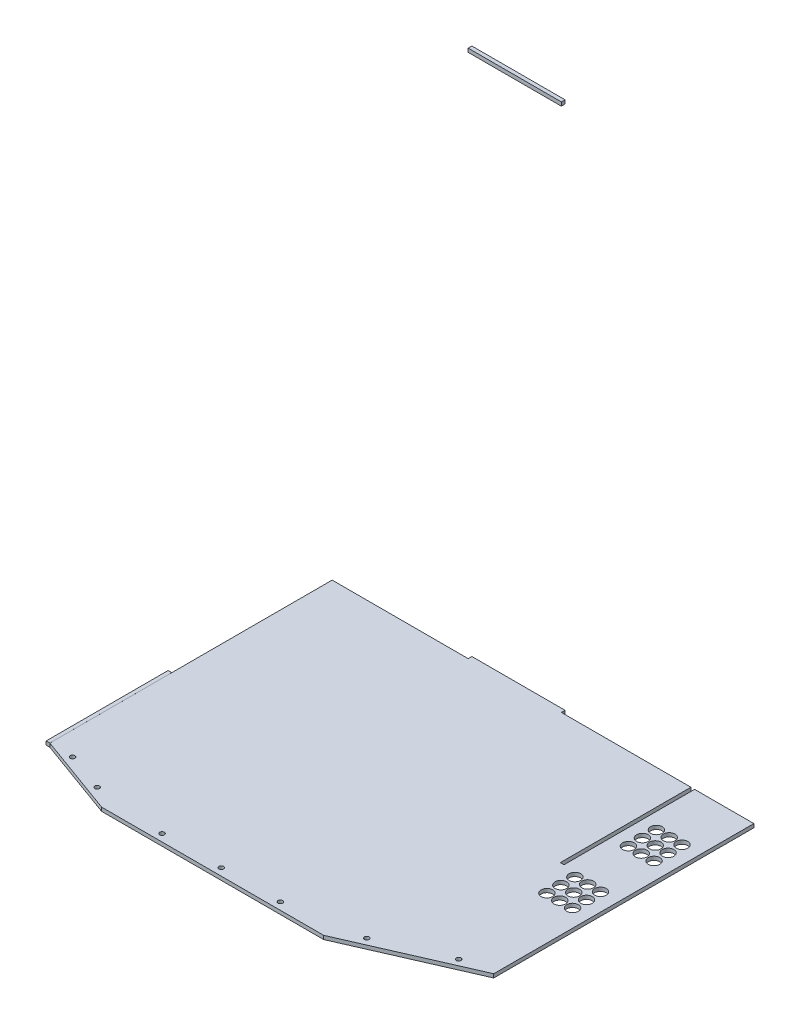
SolidWorks part; units mm, degrees
material "6061-T6 (SS)"
ref_plane "X-Y Datum" through (0, 0, 0) normal (0, 0, 1) x (1, 0, 0)
ref_plane "X-Z Datum" through (0, 0, 0) normal (0, 1, 0) x (1, 0, 0)
ref_plane "Y-Z Datum" through (0, 0, 0) normal (1, 0, 0) x (0, 0, -1)
sketch "Sketch1" plane through (0, 0, 0) normal (0, 0, 1) x (1, 0, 0)
  line L1 (-154.0556, -1.5875) -> (154.0556, -1.5875)
  line L2 (-154.0556, -1.5875) -> (-154.0556, 1.5875)
  line L3 (-154.0556, 1.5875) -> (154.0556, 1.5875)
  line L4 (154.0556, -1.5875) -> (154.0556, 1.5875)
  line L5 (-154.0556, -1.5875) -> (154.0556, 1.5875) construction
  line L6 (-154.0556, 1.5875) -> (154.0556, -1.5875) construction
  point P0 (0, 0)
  dimension "D1" = 3.175
  dimension "D2" = 308.1112
extrude "Boss-Extrude1" add sketch "Sketch1" along normal blind 267.83
sketch "Sketch3" plane through (154.0556, 0, 0) normal (1, 0, 0) x (0, 0, -1)
  line L0 (-267.83, 1.5875) -> (0, 1.5875) construction
  line L1 (-267.83, -1.5875) -> (-112.128, -1.5875)
  line L2 (-267.83, -1.5875) -> (-267.83, 1.5875)
  line L3 (-267.83, 1.5875) -> (-112.128, 1.5875)
  line L4 (-112.128, -1.5875) -> (-112.128, 1.5875)
  dimension "D1" = 155.702
extrude "Boss-Extrude3" add sketch "Sketch3" along normal blind 3.175
sketch "Sketch4" plane through (0, 0, 267.83) normal (0, 0, 1) x (1, 0, 0)
  line L1 (157.2306, -1.5875) -> (208.1043, -1.5875)
  line L2 (157.2306, -1.5875) -> (157.2306, 1.5875)
  line L3 (157.2306, 1.5875) -> (208.1043, 1.5875)
  line L4 (208.1043, -1.5875) -> (208.1043, 1.5875)
  dimension "D1" = 3.175
  dimension "D2" = 50.8737
extrude "Boss-Extrude4" add sketch "Sketch4" against normal blind 267.83
sketch "Sketch6" plane through (0, 1.5875, 0) normal (0, 1, 0) x (1, 0, 0)
  line L0 (106.5043, -267.83) -> (106.5043, -223.38)
  line L1 (208.1043, -267.83) -> (-154.0556, -267.83) construction
  line L2 (208.1043, -223.38) -> (106.5043, -223.38)
  line L3 (208.1043, 0) -> (208.1043, -267.83) construction
  line L4 (106.5043, -267.83) -> (208.1043, -223.38)
  line M9 (-154.0556, -267.83) -> (208.1043, -267.83)
  line M10 (208.1043, -267.83) -> (208.1043, 0)
  dimension "D1" = 44.45
  dimension "D2" = 101.6
extrude "Cut-Extrude1" cut sketch "Sketch6" against normal through all contours L4 M9 M10
sketch "Sketch11" plane through (0, -1.5875, 0) normal (0, -1, 0) x (1, 0, 0)
  line L0 (-84.2056, 267.83) -> (-84.2056, 242.43)
  line L1 (-154.0556, 267.83) -> (106.5043, 267.83) construction
  line L2 (-154.0556, 242.43) -> (-84.2056, 242.43)
  line L3 (-154.0556, 267.83) -> (-154.0556, 0) construction
  line L4 (-154.0556, 242.43) -> (-84.2056, 267.83)
  line M4 (-154.0556, 267.83) -> (-154.0556, 0)
  line M18 (106.5043, 267.83) -> (-154.0556, 267.83)
  dimension "D1" = 69.85
  dimension "D2" = 25.4
extrude "Cut-Extrude3" cut sketch "Sketch11" against normal through all contours L4 M4 M18
sketch "Sketch13" plane through (0, -1.5875, 0) normal (0, -1, 0) x (1, 0, 0)
  circle A6 centre (171.0499, 116.6448) radius 5
  circle A7 centre (182.0499, 116.6448) radius 5
  circle A8 centre (193.0499, 116.6448) radius 5
  circle A9 centre (171.0499, 46.6448) radius 5
  circle A10 centre (182.0499, 46.6448) radius 5
  circle A11 centre (193.0499, 46.6448) radius 5
extrude "Cut-Extrude4" cut sketch "Sketch13" against normal through all
pattern_linear "LPattern1" count 3 spacing 12 along (0, 0, 1) of "Cut-Extrude4"
sketch "Sketch17" plane through (-154.0556, 0, 0) normal (-1, 0, 0) x (0, 0, 1)
  line L1 (137.65, -1.577) -> (242.425, -1.577)
  line L2 (137.65, -1.577) -> (137.65, 1.598)
  line L3 (137.65, 1.598) -> (242.425, 1.598)
  line L4 (242.425, -1.577) -> (242.425, 1.598)
extrude "Boss-Extrude5" add sketch "Sketch17" along normal blind 3.175
sketch "Sketch18" plane through (0, 0, 0) normal (0, 0, -1) x (-1, 0, 0)
  line L0 (-154.0556, 1.5875) -> (154.0556, 1.5875) construction
  line L1 (-42.784, 1.5875) -> (37.216, 1.5875)
  line L2 (-42.784, 1.5875) -> (-42.784, -1.5875)
  line L3 (-42.784, -1.5875) -> (37.216, -1.5875)
  line L4 (37.216, 1.5875) -> (37.216, -1.5875)
  line L5 (-42.784, 1.5875) -> (-42.784, -1.5875) construction
  line L6 (154.0556, -1.5875) -> (-154.0556, -1.5875) construction
  line L7 (37.216, 1.5875) -> (37.216, -1.5875) construction
extrude "Boss-Extrude6" add sketch "Sketch18" along normal blind 3.175
sketch "Sketch19" plane through (0, 0, 0) normal (0, 0, -1) x (-1, 0, 0)
  line L1 (37.216, 455.6355) -> (-42.784, 455.6355)
  line L2 (37.216, 455.6355) -> (37.216, 452.4605)
  line L3 (37.216, 452.4605) -> (-42.784, 452.4605)
  line L4 (-42.784, 455.6355) -> (-42.784, 452.4605)
extrude "Boss-Extrude7" add sketch "Sketch19" along normal blind 3.175 separate body
sketch "Sketch20" plane through (0, -1.5875, 0) normal (0, -1, 0) x (1, 0, 0)
  circle A0 centre (182.2431, 227.6374) radius 2 construction
  circle A1 centre (127.1646, 251.4366) radius 2 construction
  circle A2 centre (63.0495, 261.5116) radius 2 construction
  circle A3 centre (12.2495, 261.5116) radius 2 construction
  circle A4 centre (-38.5505, 261.5116) radius 2 construction
  circle A5 centre (-100.9036, 255.0014) radius 2 construction
  circle A6 centre (-133.9829, 242.9725) radius 2 construction
  circle A7 centre (182.2431, 227.6374) radius 2
  circle A8 centre (127.1646, 251.4366) radius 2
  circle A9 centre (63.0495, 261.5116) radius 2
  circle A10 centre (12.2495, 261.5116) radius 2
  circle A11 centre (-38.5505, 261.5116) radius 2
  circle A12 centre (-100.9036, 255.0014) radius 2
  circle A13 centre (-133.9829, 242.9725) radius 2
extrude "Cut-Extrude5" cut sketch "Sketch20" against normal blind 3.175
